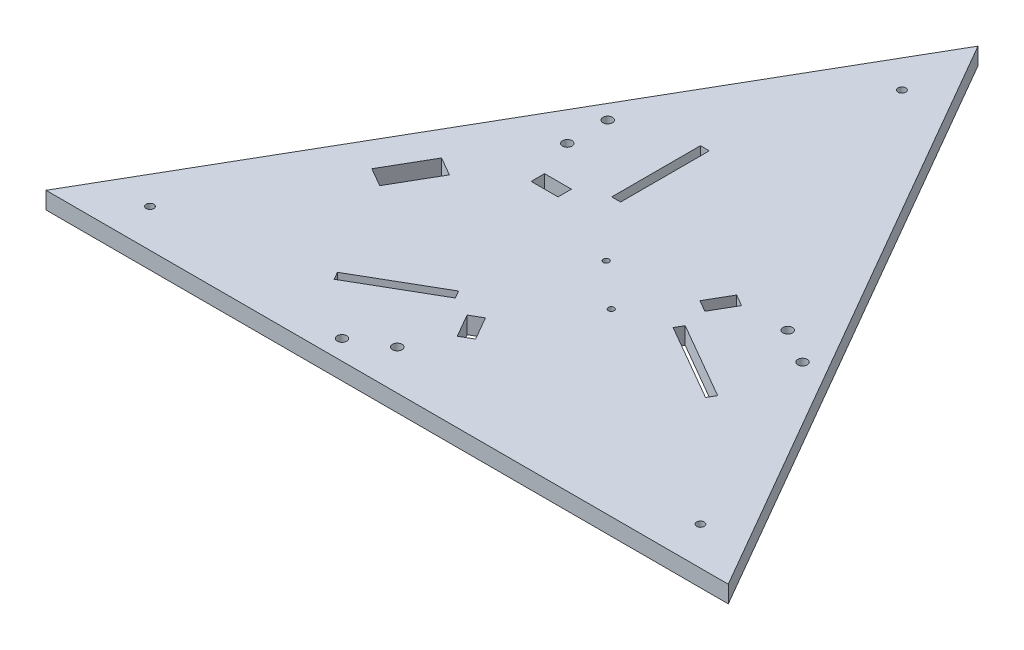
SolidWorks part; units mm, degrees
ref_plane "Front Plane" through (0, 0, 0) normal (0, 0, 1) x (1, 0, 0)
ref_plane "Top Plane" through (0, 0, 0) normal (0, 1, 0) x (1, 0, 0)
ref_plane "Right Plane" through (0, 0, 0) normal (1, 0, 0) x (0, 0, -1)
sketch "Sketch1" plane through (0, 0, 0) normal (0, 1, 0) x (1, 0, 0)
  line L1 (0, 146.647) -> (-127, -73.3235)
  line L2 (-127, -73.3235) -> (127, -73.3235)
  line L3 (127, -73.3235) -> (0, 146.647)
  circle A0 centre (0, 0) radius 73.3235 construction
  dimension "D1" = 254
extrude "Boss-Extrude1" add sketch "Sketch1" along normal blind 6.35
sketch "Sketch2" plane through (0, 6.35, 0) normal (0, 1, 0) x (1, 0, 0)
  line L0 (0, 29.8527) -> (0, 146.647)
  line L1 (51.7064, 29.8527) -> (-51.7064, 29.8527)
  line L2 (-51.7064, 29.8527) -> (0, -59.7054)
  line L3 (0, -59.7054) -> (51.7064, 29.8527)
  line L4 (-25.8532, -14.9264) -> (-127, -73.3235)
  line L5 (25.8532, -14.9264) -> (127, -73.3235)
  line L6 (0, 146.647) -> (-127, -73.3235) construction
  line L7 (-63.802, 10.7387) -> (-56.8738, 6.7387)
  line L8 (-63.802, 10.7387) -> (-73.302, -5.7158)
  line L9 (-73.302, -5.7158) -> (-66.3738, -9.7158)
  line L10 (-56.8738, 6.7387) -> (-66.3738, -9.7158)
  circle A0 centre (0, 0) radius 29.8527 construction
  line B0 (-44.7064, 46.3627) -> (-51.7064, 46.3627) construction
  line B1 (-37.558, 39.2143) -> (-37.558, 32.2143) construction
  line B2 (-37.558, 53.5111) -> (-37.558, 60.5111) construction
  line B3 (-37.558, 46.3627) -> (-42.6127, 41.308) construction
  line B4 (-42.6127, 41.308) -> (-47.5624, 36.3583) construction
  line B5 (-37.558, 46.3627) -> (-32.5033, 41.308) construction
  line B6 (-32.5033, 41.308) -> (-27.5536, 36.3583) construction
  line B7 (-37.558, 46.3627) -> (-42.6127, 51.4174) construction
  line B8 (-42.6127, 51.4174) -> (-47.5624, 56.3671) construction
  line B9 (-37.558, 46.3627) -> (-32.5033, 51.4174) construction
  line B10 (-32.5033, 51.4174) -> (-27.5536, 56.3671) construction
  line B11 (-30.4096, 46.3627) -> (-23.4096, 46.3627) construction
  line B12 (-19.558, 29.8527) -> (-19.558, 62.8727)
  line B13 (-29.558, 29.8527) -> (-29.558, 62.8727)
  line B14 (-29.558, 29.8527) -> (-19.558, 29.8527)
  line B15 (-19.558, 29.8527) -> (-19.558, 62.8727)
  line B16 (-29.558, 62.8727) -> (-19.558, 62.8727)
  line B17 (-19.558, 29.8527) -> (-16.256, 29.8527)
  line B18 (-19.558, 62.8727) -> (-16.256, 62.8727)
  line B19 (-16.256, 29.8527) -> (-16.256, 62.8727)
  line B20 (-16.256, 29.8527) -> (-16.256, 62.8727)
  line B21 (-16.256, 29.8527) -> (0, 29.8527)
  line B22 (-16.256, 62.8727) -> (0, 62.8727)
  line B23 (0, 29.8527) -> (0, 62.8727)
  line B24 (-23.4096, 46.3627) -> (-19.558, 46.3627) construction
  circle B25 centre (-37.558, 46.3627) radius 7.1484
  circle B26 centre (-37.558, 46.3627) radius 14.1484
  circle B27 centre (-37.558, 35.7143) radius 1.397
  circle B28 centre (-30.0284, 38.8331) radius 1.778
  circle B29 centre (-30.0284, 53.8923) radius 1.778
  circle B30 centre (-37.558, 57.0111) radius 1.397
  circle B31 centre (-45.0876, 53.8923) radius 1.778
  circle B32 centre (-48.2064, 46.3627) radius 1.397
  circle B33 centre (-45.0876, 38.8331) radius 1.778
  circle B34 centre (-26.9096, 46.3627) radius 1.397
  line B35 (-17.7981, -61.8982) -> (-14.2981, -67.9604) construction
  line B36 (-15.1816, -52.1333) -> (-9.1194, -48.6333) construction
  line B37 (-27.563, -59.2817) -> (-33.6251, -62.7817) construction
  line B38 (-21.3723, -55.7075) -> (-14.4675, -57.5577) construction
  line B39 (-14.4675, -57.5577) -> (-7.706, -59.3694) construction
  line B40 (-21.3723, -55.7075) -> (-19.5221, -48.8027) construction
  line B41 (-19.5221, -48.8027) -> (-17.7104, -42.0412) construction
  line B42 (-21.3723, -55.7075) -> (-23.2224, -62.6124) construction
  line B43 (-23.2224, -62.6124) -> (-25.0342, -69.3738) construction
  line B44 (-21.3723, -55.7075) -> (-28.2771, -53.8574) construction
  line B45 (-28.2771, -53.8574) -> (-35.0386, -52.0457) construction
  line B46 (-24.9465, -49.5168) -> (-28.4465, -43.4547) construction
  line B47 (-16.0742, -31.8641) -> (-44.6704, -48.3741)
  line B48 (-11.0742, -40.5243) -> (-39.6704, -57.0343)
  line B49 (-11.0742, -40.5243) -> (-16.0742, -31.8641)
  line B50 (-16.0742, -31.8641) -> (-44.6704, -48.3741)
  line B51 (-39.6704, -57.0343) -> (-44.6704, -48.3741)
  line B52 (-16.0742, -31.8641) -> (-17.7252, -29.0045)
  line B53 (-44.6704, -48.3741) -> (-46.3214, -45.5145)
  line B54 (-17.7252, -29.0045) -> (-46.3214, -45.5145)
  line B55 (-17.7252, -29.0045) -> (-46.3214, -45.5145)
  line B56 (-17.7252, -29.0045) -> (-25.8532, -14.9264)
  line B57 (-46.3214, -45.5145) -> (-54.4494, -31.4364)
  line B58 (-25.8532, -14.9264) -> (-54.4494, -31.4364)
  line B59 (-28.4465, -43.4547) -> (-30.3723, -40.1191) construction
  circle B60 centre (-21.3723, -55.7075) radius 7.1484
  circle B61 centre (-21.3723, -55.7075) radius 14.1484
  circle B62 centre (-12.1505, -50.3833) radius 1.397
  circle B63 centre (-18.6163, -45.422) radius 1.778
  circle B64 centre (-31.6578, -52.9515) radius 1.778
  circle B65 centre (-30.5941, -61.0317) radius 1.397
  circle B66 centre (-24.1283, -65.9931) radius 1.778
  circle B67 centre (-16.0481, -64.9293) radius 1.397
  circle B68 centre (-11.0867, -58.4635) radius 1.778
  circle B69 centre (-26.6965, -46.4858) radius 1.397
  line B70 (62.5045, 15.5355) -> (66.0045, 21.5977) construction
  line B71 (52.7396, 12.919) -> (46.6774, 16.419) construction
  line B72 (65.121, 5.7706) -> (71.1831, 2.2706) construction
  line B73 (58.9303, 9.3448) -> (57.0801, 16.2497) construction
  line B74 (57.0801, 16.2497) -> (55.2684, 23.0111) construction
  line B75 (58.9303, 9.3448) -> (52.0255, 7.4947) construction
  line B76 (52.0255, 7.4947) -> (45.264, 5.683) construction
  line B77 (58.9303, 9.3448) -> (65.8351, 11.195) construction
  line B78 (65.8351, 11.195) -> (72.5966, 13.0067) construction
  line B79 (58.9303, 9.3448) -> (60.7804, 2.44) construction
  line B80 (60.7804, 2.44) -> (62.5922, -4.3215) construction
  line B81 (55.3561, 3.1541) -> (51.8561, -2.908) construction
  line B82 (35.6322, 2.0114) -> (64.2284, -14.4986)
  line B83 (40.6322, 10.6716) -> (69.2284, -5.8384)
  line B84 (40.6322, 10.6716) -> (35.6322, 2.0114)
  line B85 (35.6322, 2.0114) -> (64.2284, -14.4986)
  line B86 (69.2284, -5.8384) -> (64.2284, -14.4986)
  line B87 (35.6322, 2.0114) -> (33.9812, -0.8482)
  line B88 (64.2284, -14.4986) -> (62.5774, -17.3582)
  line B89 (33.9812, -0.8482) -> (62.5774, -17.3582)
  line B90 (33.9812, -0.8482) -> (62.5774, -17.3582)
  line B91 (33.9812, -0.8482) -> (25.8532, -14.9264)
  line B92 (62.5774, -17.3582) -> (54.4494, -31.4364)
  line B93 (25.8532, -14.9264) -> (54.4494, -31.4364)
  line B94 (51.8561, -2.908) -> (49.9303, -6.2436) construction
  circle B95 centre (58.9303, 9.3448) radius 7.1484
  circle B96 centre (58.9303, 9.3448) radius 14.1484
  circle B97 centre (49.7085, 14.669) radius 1.397
  circle B98 centre (48.6447, 6.5888) radius 1.778
  circle B99 centre (61.6863, -0.9407) radius 1.778
  circle B100 centre (68.1521, 4.0206) radius 1.397
  circle B101 centre (69.2158, 12.1008) radius 1.778
  circle B102 centre (64.2545, 18.5666) radius 1.397
  circle B103 centre (56.1743, 19.6304) radius 1.778
  circle B104 centre (53.6061, 0.1231) radius 1.397
  dimension "D1" = 19
  dimension "D2" = 8
  dimension "D3" = 12.7
sketch_block_instance "Servo_Brackets_BlockV2-1"
sketch_block "Servo_Brackets_BlockV2" parameters "D2"=2.794, "D3"=3.556, "D1"=7, "D4"=10, "D5"=33.02, "D6"=3.302, "D7"=16.256, "D8"=18
sketch_block_instance "Servo_Brackets_BlockV2-2"
sketch_block_instance "Servo_Brackets_BlockV2-3"
extrude "Cut-Extrude1" cut sketch "Sketch2" against normal through all contours L1 B19 B18 B12 | L2 B54 B53 B47 | B68 | B66 | L3 B89 B88 B82 | B103 | B101 | L10 L7 L8 L9 | B31 | B33
sketch "Sketch3" plane through (0, 6.35, 0) normal (0, 1, 0) x (1, 0, 0)
  line L0 (63.5, 36.6617) -> (51.4016, 29.6767)
  line L1 (22.225, 108.1521) -> (104.775, -34.8287)
  line L2 (22.225, 108.1521) -> (10.1266, 101.1671)
  line L3 (10.1266, 101.1671) -> (92.6766, -41.8137)
  line L4 (104.775, -34.8287) -> (92.6766, -41.8137)
  line L5 (-63.5, 36.6617) -> (-51.4016, 29.6767)
  line L6 (-104.775, -34.8287) -> (-22.225, 108.1521)
  line L7 (-104.775, -34.8287) -> (-92.6766, -41.8137)
  line L8 (-92.6766, -41.8137) -> (-10.1266, 101.1671)
  line L9 (-22.225, 108.1521) -> (-10.1266, 101.1671)
  line L10 (0, -59.3535) -> (0, -73.3235)
  line L11 (-82.55, -59.3535) -> (82.55, -59.3535)
  line L12 (-82.55, -59.3535) -> (-82.55, -73.3235)
  line L13 (-82.55, -73.3235) -> (82.55, -73.3235)
  line L14 (82.55, -59.3535) -> (82.55, -73.3235)
  line L15 (127, -73.3235) -> (0, 146.647) construction
  line L16 (0, 146.647) -> (-127, -73.3235) construction
  line L17 (-127, -73.3235) -> (127, -73.3235) construction
  line L18 (-22.225, 108.1521) -> (22.225, 108.1521)
  line L19 (-104.775, -34.8287) -> (-82.55, -73.3235)
  line L20 (104.775, -34.8287) -> (82.55, -73.3235)
  line L21 (35.3209, 21.4723) -> (30.3209, 12.812)
  line L22 (-29.558, 24.8527) -> (-39.558, 24.8527)
  line L23 (-29.558, 24.8527) -> (-29.558, 19.8527)
  line L24 (-29.558, 19.8527) -> (-39.558, 19.8527)
  line L25 (-39.558, 24.8527) -> (-39.558, 19.8527)
  line L26 (35.3209, 21.4723) -> (39.6511, 18.9723)
  line L27 (39.6511, 18.9723) -> (34.6511, 10.312)
  line L28 (30.3209, 12.812) -> (34.6511, 10.312)
  line L29 (0.9351, -41.325) -> (-4.0649, -32.6647)
  line L30 (0.9351, -41.325) -> (-3.3951, -43.825)
  line L31 (-3.3951, -43.825) -> (-8.3951, -35.1647)
  line L32 (-4.0649, -32.6647) -> (-8.3951, -35.1647)
  line L33 (-16.256, 29.8527) -> (-19.558, 29.8527) construction
  line L34 (33.9812, -0.8482) -> (35.6322, 2.0114) construction
  line L35 (-17.7252, -29.0045) -> (-16.0742, -31.8641) construction
  line L36 (-19.558, 29.8527) -> (-19.558, 62.8727) construction
  line L37 (33.9812, -0.8482) -> (62.5774, -17.3582) construction
  line L38 (-17.7252, -29.0045) -> (-46.3214, -45.5145) construction
  circle A0 centre (102.4613, -59.1561) radius 1.4224
  circle A1 centre (0, 118.3121) radius 1.4224
  circle A2 centre (-102.4613, -59.1561) radius 1.4224
  point P51 (-17.907, 29.8527)
  dimension "D7" = 2.8448
  dimension "D20" = 10.16
  dimension "D1" = 165.1
  dimension "D2" = 10.16
  dimension "D3" = 165.1
  dimension "D4" = 13.97
  dimension "D5" = 165.1
  dimension "D6" = 13.97
  dimension "D8" = 10
  dimension "D9" = 5
  dimension "D10" = 10
  dimension "D11" = 5
  dimension "D12" = 10
  dimension "D13" = 5
  dimension "D14" = 10
  dimension "D15" = 5
  dimension "D16" = 10
  dimension "D17" = 5
  dimension "D18" = 10
  dimension "D19" = 5
  dimension "D21" = 10.16
extrude "Cut-Extrude2" cut sketch "Sketch3" against normal through all contours A1 | A2 | A0 | L22 L25 L24 L23 | L29 L32 L31 L30 | L21 L28 L27 L26
sketch "Sketch4" plane through (0, 6.35, 0) normal (0, 1, 0) x (1, 0, 0)
  line L1 (16.51, -6.3973) -> (16.51, 8.2077) construction
  line L2 (16.51, -6.3973) -> (0, -6.3973) construction
  line L3 (0, -6.3973) -> (0, 8.2077) construction
  line L4 (16.51, 8.2077) -> (0, 8.2077) construction
  circle A0 centre (0, 8.2077) radius 1.0922
  circle A1 centre (16.51, -6.3973) radius 1.0922
  dimension "D3" = 2.1844
  dimension "D4" = 2.1844
  dimension "D1" = 14.605
  dimension "D2" = 16.51
extrude "Cut-Extrude3" cut sketch "Sketch4" against normal through all
